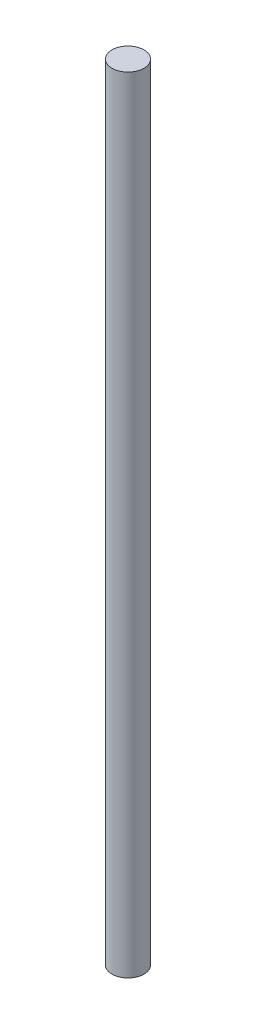
SolidWorks part; units mm, degrees
ref_plane "Front Plane" through (0, 0, 0) normal (0, 0, 1) x (1, 0, 0)
ref_plane "Top Plane" through (0, 0, 0) normal (0, 1, 0) x (1, 0, 0)
ref_plane "Right Plane" through (0, 0, 0) normal (1, 0, 0) x (0, 0, -1)
sketch "Sketch2" plane through (0, 0, 0) normal (0, 1, 0) x (1, 0, 0)
  circle A0 centre (0, 0) radius 0.815
  dimension "D1" = 1.63
extrude "Boss-Extrude1" add sketch "Sketch2" along normal blind 40
